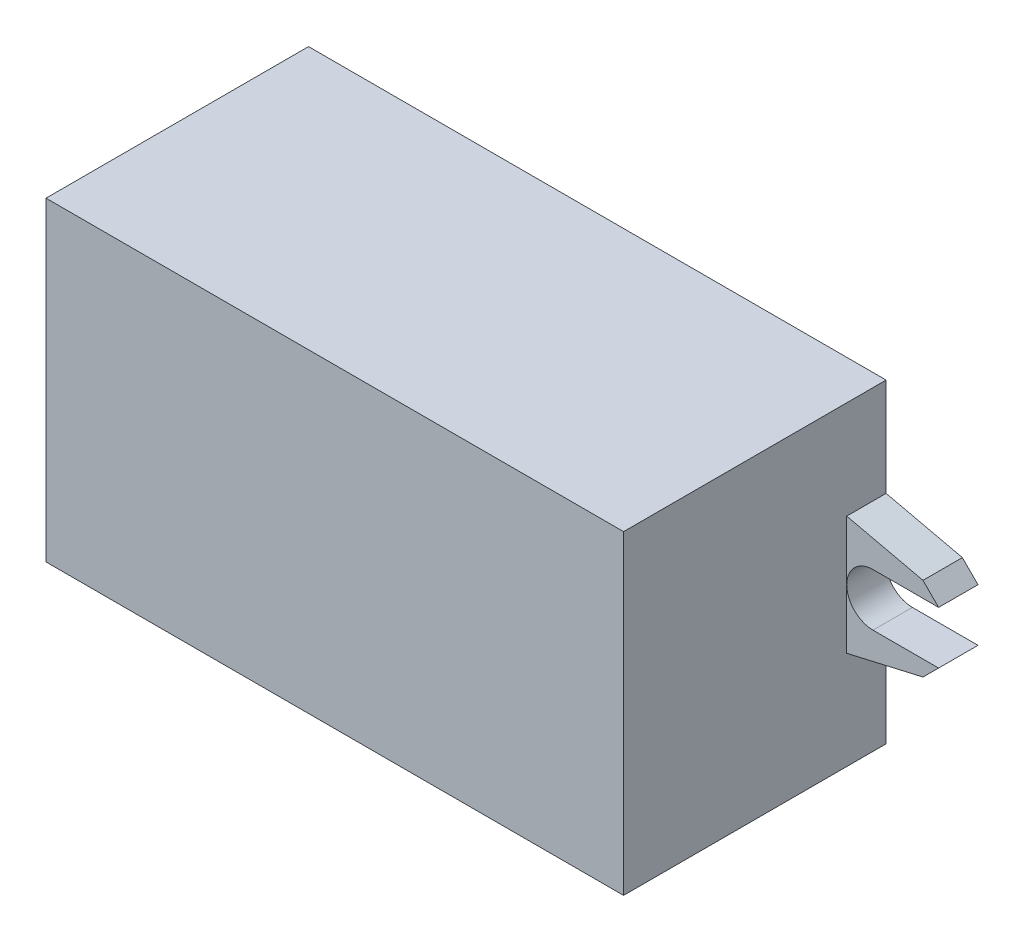
SolidWorks part; units mm, degrees
ref_plane "前视基准面" through (0, 0, 0) normal (0, 0, 1) x (1, 0, 0)
ref_plane "上视基准面" through (0, 0, 0) normal (0, 1, 0) x (1, 0, 0)
ref_plane "右视基准面" through (0, 0, 0) normal (1, 0, 0) x (0, 0, -1)
other "Configuration Table"
sketch "草图1" plane through (0, 0, 0) normal (0, 0, 1) x (1, 0, 0)
  line L1 (22, -12) -> (-22, -12)
  line L2 (22, -12) -> (22, 12)
  line L3 (22, 12) -> (-22, 12)
  line L4 (-22, -12) -> (-22, 12)
  line L5 (22, -12) -> (-22, 12) construction
  line L6 (22, 12) -> (-22, -12) construction
  point P0 (0, 0)
  dimension "D1" = 44
  dimension "D2" = 24
extrude "凸台-拉伸1" add sketch "草图1" along normal blind 20
sketch "草图2" plane through (0, 0, 0) normal (0, 0, -1) x (-1, 0, 0)
  line L0 (29, 0) -> (-29, 0) construction
  line L1 (-22, -12) -> (-22, 12) construction
  line L2 (22, 12) -> (22, -12) construction
  line L3 (-29, 2) -> (-24, 2)
  line L4 (-29, 2) -> (-27.8092, 3.1908)
  line L5 (-27.8092, 3.1908) -> (-22, 4.5236)
  line L6 (-29, -2) -> (-24, -2)
  line L7 (-29, -2) -> (-27.8092, -3.1908)
  line L8 (-27.8092, -3.1908) -> (-22, -4.5236)
  line L9 (0, 0) -> (0, -5.6315)
  line L10 (27.8092, -3.1908) -> (22, -4.5236)
  line L11 (29, -2) -> (27.8092, -3.1908)
  line L12 (29, -2) -> (24, -2)
  line L13 (27.8092, 3.1908) -> (22, 4.5236)
  line L14 (29, 2) -> (27.8092, 3.1908)
  line L15 (29, 2) -> (24, 2)
  line L16 (-22, 4.5236) -> (-22, -4.5236)
  line L17 (22, 4.5236) -> (22, -4.5236)
  arc A0 (-24, -2) -> (-24, 2) centre (-24, 0) ccw
  arc A1 (24, 2) -> (24, -2) centre (24, 0) ccw
  arc A2 (24, -2) -> (24, 2) centre (24, 0) cw
  point P4 (0, 0)
  line M8 (22, -12) -> (22, 12)
  line M10 (-22, 12) -> (-22, -12)
  dimension "D1" = 58
extrude "凸台-拉伸2" add sketch "草图2" against normal blind 3 contours A1 L15 L14 L13 L17 | A1 L10 L11 L12 M8 | A0 L5 L4 L3 M10 | A0 L6 L7 L8 L16
